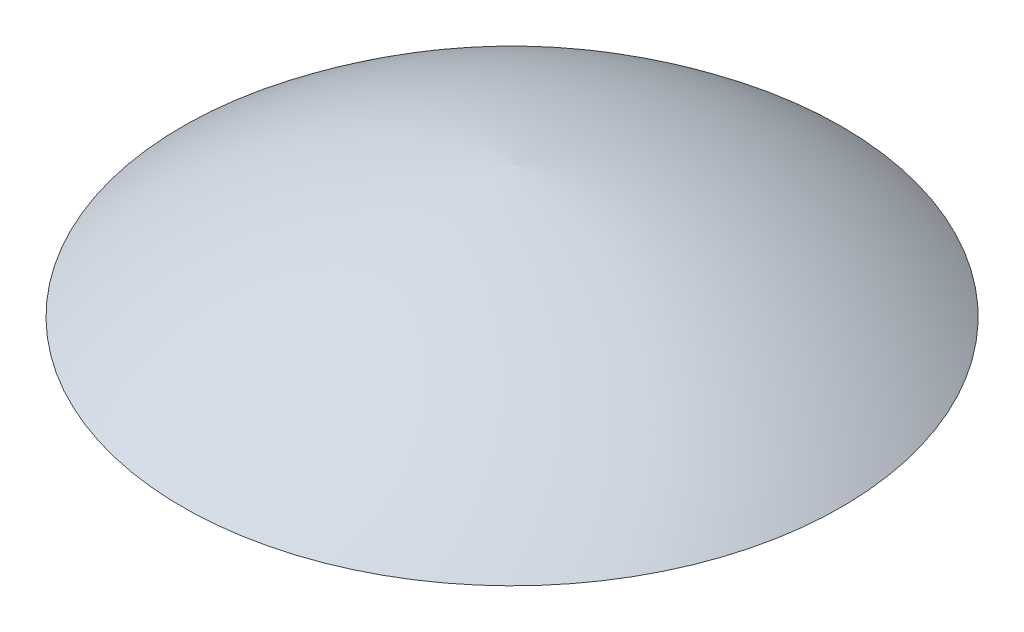
SolidWorks part; units mm, degrees
ref_plane "Front Plane" through (0, 0, 0) normal (0, 0, 1) x (1, 0, 0)
ref_plane "Top Plane" through (0, 0, 0) normal (0, 1, 0) x (1, 0, 0)
ref_plane "Right Plane" through (0, 0, 0) normal (1, 0, 0) x (0, 0, -1)
sketch "Sketch3" plane through (0, 0, 0) normal (1, 0, 0) x (0, 0, -1)
  line L1 (0, 0) -> (32.5, 0)
  line L3 (0, 0) -> (0, 13)
  arc A0 (0, 13) -> (32.5, 0) centre (-5.0644, -46.7859) cw
  point P0 (-5.0644, -46.7859)
  dimension "D2" = 60
  dimension "D1" = 32.5
  dimension "D3" = 13
revolve "Revolve5" add sketch "Sketch3" angle 360 about L3
